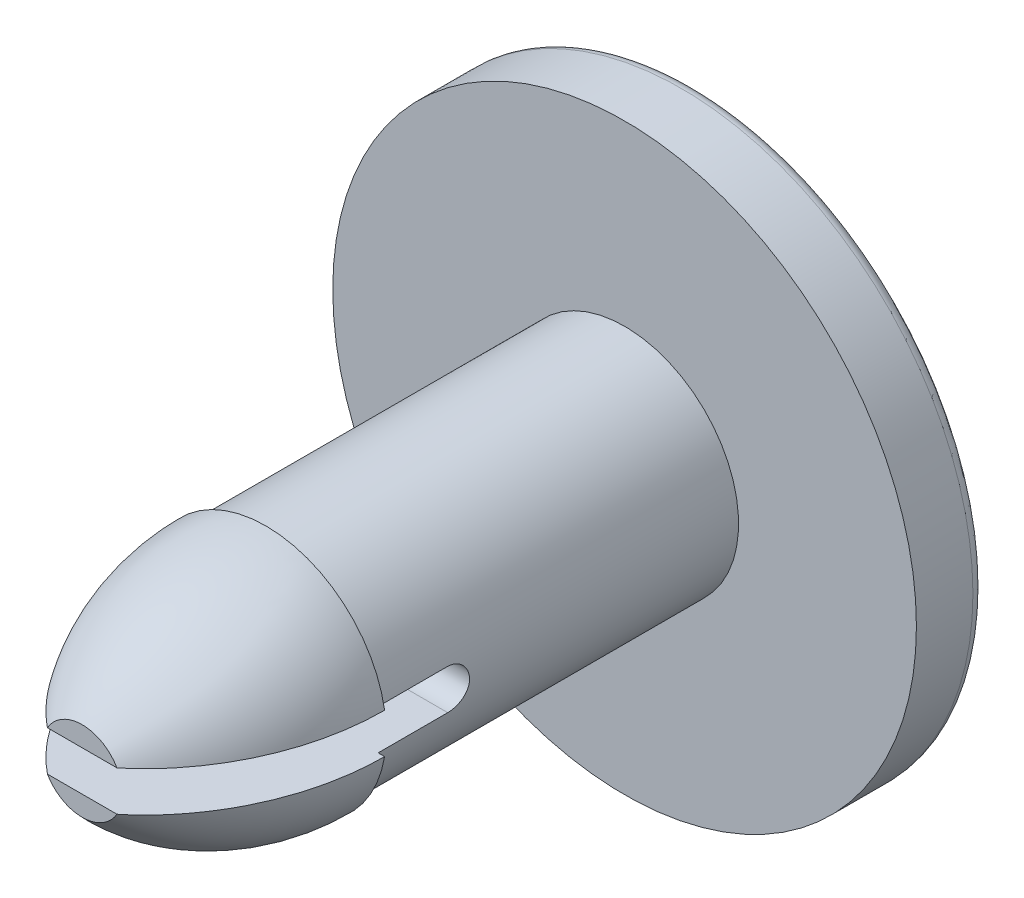
SolidWorks part; units mm, degrees
ref_plane "Front" through (0, 0, 0) normal (0, 0, 1) x (1, 0, 0)
ref_plane "Top" through (0, 0, 0) normal (0, 1, 0) x (1, 0, 0)
ref_plane "Right" through (0, 0, 0) normal (1, 0, 0) x (0, 0, -1)
sketch "Layout" plane through (0, 0, 0) normal (1, 0, 0) x (0, 0, -1)
  line L0 (-15.7988, 0) -> (0, 0) construction
  line L1 (0, 7.5438) -> (0, -7.5438) construction
  line L2 (0, 3.1115) -> (-11.049, 3.1115) construction
  line L3 (-1.778, 0) -> (-1.778, 7.5438) construction
  line L4 (-1.778, 7.5438) -> (0, 7.5438) construction
  line L5 (-11.049, 3.1115) -> (-15.7988, 3.1115) construction
  circle A0 centre (-15.7988, 0) radius 3.1242 construction
  dimension "Drill Size " = 6.2484
  dimension "Length" = 14.0208
  dimension "Head Diameter" = 15.0876
  dimension "Head Height" = 1.778
  dimension "For Material Thickness " = 9.271
  dimension "For Hole Size" = 6.223
sketch "Sketch2" plane through (0, 0, 0) normal (1, 0, 0) x (0, 0, -1)
  line L0 (0, 0) -> (-15.7988, 0)
  line L1 (-15.7988, 0) -> (-15.7988, 1.0372)
  line L2 (-11.049, 3.1115) -> (-4.6456, 3.1115) construction
  line L3 (-11.049, 3.1115) -> (-11.049, 2.9464)
  line L4 (-11.049, 2.9464) -> (-1.778, 2.9464)
  line L7 (-1.778, 2.9464) -> (-1.778, 7.5438)
  line L8 (-1.778, 7.5438) -> (0, 7.5438)
  line L9 (0, 7.5438) -> (0, 0)
  line L10 (-11.049, 3.1115) -> (-15.7988, 3.1115) construction
  line L12 (-15.7988, 0) -> (-4.6456, 0) construction
  line L14 (-15.7988, 0) -> (-6.9144, 0) construction
  line L15 (-11.049, 3.1115) -> (-11.049, 2.0743) construction
  line L16 (-11.049, 2.0743) -> (-11.049, 1.0372) construction
  line L17 (-11.049, 1.0372) -> (-11.049, 0) construction
  line L18 (-11.049, 1.0372) -> (-18.4523, 1.0372) construction
  line L19 (-1.778, 0) -> (-1.778, 7.5438) construction
  arc A0 (-15.7988, 1.0372) -> (-11.049, 3.1115) centre (-11.049, -3.3637) cw
  dimension "D1" = 0.1651
revolve "Revolve1" add sketch "Sketch2" angle 360 about L0
sketch "Sketch3" plane through (0, 0, 0) normal (1, 0, 0) x (0, 0, -1)
  line L0 (-11.049, 0) -> (-8.7312, 0) construction
  line L2 (-11.049, -2.9464) -> (-11.049, 2.9464) construction
  line L3 (-8.7312, 0) -> (-6.4135, 0) construction
  line L4 (-15.7988, 1.0372) -> (-15.7988, 0) construction
  line L6 (-6.4135, 0) -> (-4.0957, 0) construction
  line L7 (-4.0957, 0) -> (-1.778, 0) construction
  line L8 (-1.778, 2.9464) -> (-1.778, -2.9464) construction
  line L9 (-15.7988, 0.5186) -> (-8.7312, 0.5186) construction
  line L10 (-9.2498, 0.5186) -> (-15.7988, 0.5186)
  line L11 (-9.2498, -0.5186) -> (-15.7988, -0.5186)
  line L12 (-15.7988, 1.0372) -> (-15.7988, -1.0372) construction
  line L13 (-15.7988, -0.5186) -> (-15.7988, 0.5186)
  arc A0 (-9.2498, -0.5186) -> (-9.2498, 0.5186) centre (-9.2498, 0) ccw
extrude "Slot" cut sketch "Sketch3" against normal through all both and the other way through all
fillet "Fillet1" radius 0.3175 1 edges at (-7.5438, 0, 0)
